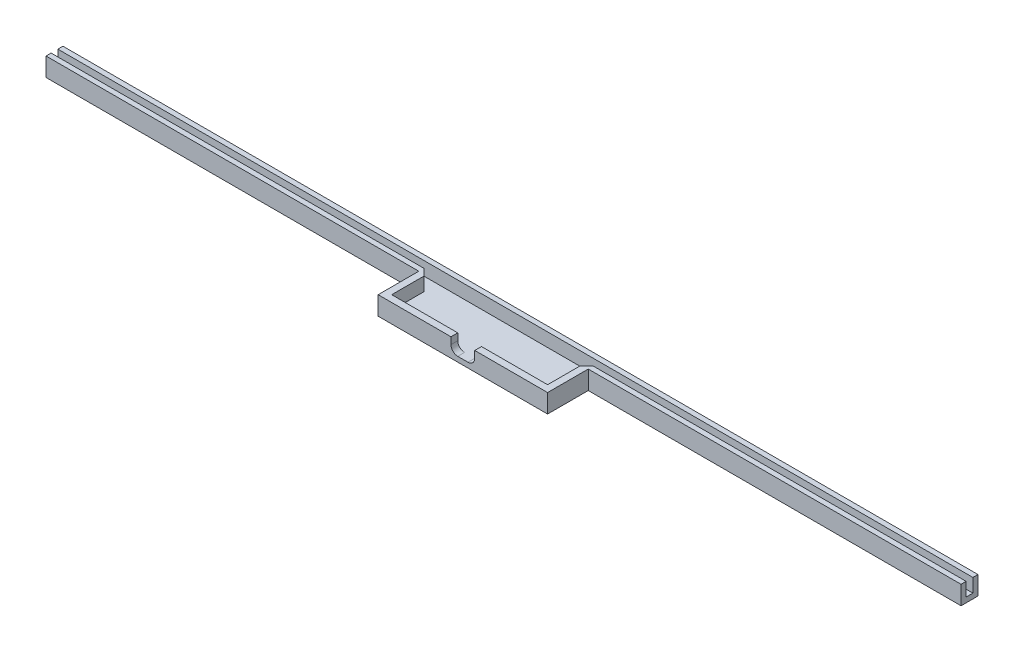
SolidWorks part; units mm, degrees
ref_plane "Front Plane" through (0, 0, 0) normal (0, 0, 1) x (1, 0, 0)
ref_plane "Top Plane" through (0, 0, 0) normal (0, 1, 0) x (1, 0, 0)
ref_plane "Right Plane" through (0, 0, 0) normal (1, 0, 0) x (0, 0, -1)
sketch "Sketch1" plane through (0, 0, 0) normal (0, 1, 0) x (1, 0, 0)
  line L0 (25, 8.5) -> (135, 8.5)
  line L1 (-25, -8.5) -> (25, -8.5)
  line L2 (-25, -8.5) -> (-25, 3.5)
  line L3 (-25, 8.5) -> (25, 8.5)
  line L4 (25, -8.5) -> (25, 3.5)
  line L5 (-25, -8.5) -> (25, 8.5) construction
  line L6 (-25, 8.5) -> (25, -8.5) construction
  line L7 (135, 8.5) -> (135, 3.5)
  line L8 (135, 3.5) -> (25, 3.5)
  line L9 (0, 0) -> (0, 53.9136) construction
  line L11 (-135, 8.5) -> (-135, 3.5)
  line L12 (-135, 3.5) -> (-25, 3.5)
  line L13 (-25, 8.5) -> (-135, 8.5)
  point P0 (0, 0)
  dimension "D1" = 50
  dimension "D2" = 17
  dimension "D3" = 110
  dimension "D4" = 5
  dimension "D5" = 90
extrude "Boss-Extrude1" add sketch "Sketch1" along normal blind 1.5
sketch "Sketch3" plane through (0, 1.5, 0) normal (0, 1, 0) x (1, 0, 0)
  line L0 (-135, 7) -> (135, 7)
  line L1 (-135, 8.5) -> (-135, 3.5) construction
  line L2 (135, 7) -> (135, 8.5)
  line L3 (135, 8.5) -> (-135, 8.5)
  line L4 (-135, 8.5) -> (-135, 7)
  dimension "D1" = 1.5
extrude "Boss-Extrude2" add sketch "Sketch3" along normal blind 4
sketch "Sketch4" plane through (0, 1.5, 0) normal (0, 1, 0) x (1, 0, 0)
  line L0 (-135, 5) -> (-25, 5)
  line L1 (-135, 7) -> (-135, 3.5) construction
  line L2 (-25, 5) -> (-25, 3.5)
  line L3 (-25, 3.5) -> (-135, 3.5)
  line L4 (-135, 5) -> (-135, 3.5)
  dimension "D1" = 1.5
extrude "Boss-Extrude3" add sketch "Sketch4" along normal blind 4
mirror "Mirror1" about plane through (0, 0, 0) normal (1, 0, 0) of "Boss-Extrude3", "Boss-Extrude2"
sketch "Sketch6" plane through (0, 1.5, 0) normal (0, 1, 0) x (1, 0, 0)
  line L0 (-25, -8.5) -> (25, -8.5) construction
  line L1 (-25, 5) -> (-23, 5)
  line L2 (-25, 5) -> (-25, -8.5)
  line L3 (-25, -8.5) -> (-23, -8.5)
  line L4 (-23, 5) -> (-23, -8.5)
  line L6 (25, 5) -> (23, 5)
  line L7 (25, 5) -> (25, -8.5)
  line L8 (25, -8.5) -> (23, -8.5)
  line L9 (23, 5) -> (23, -8.5)
  dimension "D1" = 2
  dimension "D2" = 2
extrude "Boss-Extrude5" add sketch "Sketch6" along normal blind 4
sketch "Sketch7" plane through (0, 1.5, 0) normal (0, 1, 0) x (1, 0, 0)
  line L0 (-23, -8.5) -> (23, -8.5) construction
  line L1 (-23, -8.5) -> (-3.5, -8.5)
  line L2 (-23, -8.5) -> (-23, -6.5)
  line L3 (-23, -6.5) -> (-3.5, -6.5)
  line L4 (-3.5, -8.5) -> (-3.5, -6.5)
  line L5 (23, -8.5) -> (3.5, -8.5)
  line L6 (23, -8.5) -> (23, -6.5)
  line L7 (23, -6.5) -> (3.5, -6.5)
  line L8 (3.5, -8.5) -> (3.5, -6.5)
  point P12 (0, -8.5)
  dimension "D1" = 2
  dimension "D2" = 2
  dimension "D3" = 3.5
  dimension "D4" = 3.5
extrude "Boss-Extrude6" add sketch "Sketch7" along normal blind 4
chamfer "Chamfer1" distance 2 angle 45 2 edges at (23, 3.5, -5) (-23, 3.5, -5)
fillet "Fillet1" radius 2 2 edges at (-3.5, 1.5, 7.5) (3.5, 1.5, 7.5)
